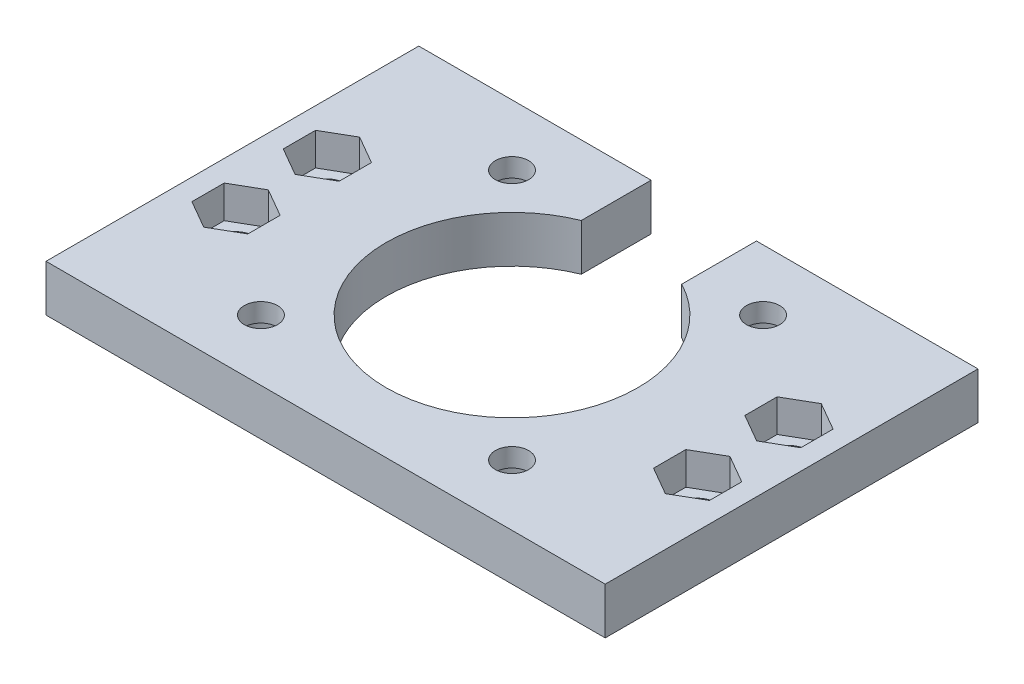
SolidWorks part; units mm, degrees
ref_plane "Front Plane" through (0, 0, 0) normal (0, 0, 1) x (1, 0, 0)
ref_plane "Top Plane" through (0, 0, 0) normal (0, 1, 0) x (1, 0, 0)
ref_plane "Right Plane" through (0, 0, 0) normal (1, 0, 0) x (0, 0, -1)
sketch "Sketch1" plane through (0, 0, 0) normal (0, 1, 0) x (1, 0, 0)
  line L1 (0, 0) -> (60, 0)
  line L2 (0, 0) -> (0, 40)
  line L3 (0, 40) -> (60, 40)
  line L4 (60, 0) -> (60, 40)
  dimension "D1" = 60
  dimension "D2" = 40
extrude "Boss-Extrude1" add sketch "Sketch1" along normal blind 5
sketch "Sketch2" plane through (0, 5, 0) normal (0, 1, 0) x (1, 0, 0)
  line L0 (30, 40) -> (30, 0)
  line L1 (60, 40) -> (0, 40) construction
  line L2 (0, 0) -> (60, 0) construction
  line L3 (30, 0) -> (30, 20)
  line L4 (30, 20) -> (60, 20)
  line L5 (60, 0) -> (60, 40) construction
  line L6 (60, 20) -> (0, 20)
  line L7 (0, 40) -> (0, 0) construction
  line L8 (54.8187, 24.9) -> (54.8187, 15.1) construction
  circle A0 centre (43.47, 33.47) radius 1.78
  circle A1 centre (16.53, 33.47) radius 1.78
  circle A2 centre (16.53, 6.53) radius 1.78
  circle A3 centre (43.47, 6.53) radius 1.78
  circle A4 centre (54.8187, 24.9) radius 1.905
  circle A5 centre (5.2887, 24.9) radius 1.905
  circle A6 centre (5.2887, 15.1) radius 1.905
  circle A7 centre (54.8187, 15.1) radius 1.905
  dimension "D1" = 3.56
  dimension "D2" = 13.47
  dimension "D3" = 13.47
  dimension "D6" = 3.81
  dimension "D7" = 4.9
  dimension "D10" = 2
  dimension "D9" = 9.8
  dimension "D4" = 2
  dimension "D5" = 2
  dimension "D8" = 2
extrude "Cut-Extrude1" cut sketch "Sketch2" along direction (0, -1, 0) on the side against the normal blind 10
sketch "Sketch3" plane through (0, 5, 0) normal (0, 1, 0) x (1, 0, 0)
  line L0 (30, 40) -> (30, 0)
  line L1 (60, 40) -> (0, 40) construction
  line L2 (0, 0) -> (60, 0) construction
  line L4 (24.925, 27.3478) -> (36.2301, 27.3478)
  line L5 (24.925, 27.3478) -> (24.925, 48.9338)
  line L6 (24.925, 48.9338) -> (36.2301, 48.9338)
  line L7 (36.2301, 27.3478) -> (36.2301, 48.9338)
  circle A0 centre (30, 20) radius 13.5
  line M12 (60, 40) -> (0, 40)
  dimension "D1" = 27
extrude "Cut-Extrude2" cut sketch "Sketch3" along direction (0, -1, 0) on the side against the normal through all contours L0 A0 L7 L4 | L5 A0 L0 L4 | A0 L7 L0 M12 | L7 A0 L0 L4 | L0 A0 L5 L4 | A0 L0 L5 M12
sketch "Sketch7" plane through (0, 0, 0) normal (0, -1, 0) x (-1, 0, 0)
  circle A0 centre (-43.47, 6.53) radius 4.5
  circle A1 centre (-16.53, 6.53) radius 4.5
  circle A2 centre (-16.53, 33.47) radius 4.5
  circle A3 centre (-43.47, 33.47) radius 4.5
  dimension "D1" = 9
  dimension "D2" = 2
extrude "Cut-Extrude5" cut sketch "Sketch7" against normal blind 3
sketch "Sketch8" plane through (0, 5, 0) normal (0, 1, 0) x (1, 0, 0)
  line L0 (5.2887, 18.5641) -> (2.2887, 16.8321)
  line L1 (54.8187, 11.6359) -> (57.8187, 13.3679)
  line L2 (57.8187, 13.3679) -> (57.8187, 16.8321)
  line L3 (57.8187, 16.8321) -> (54.8187, 18.5641)
  line L4 (54.8187, 18.5641) -> (51.8187, 16.8321)
  line L5 (51.8187, 16.8321) -> (51.8187, 13.3679)
  line L6 (51.8187, 13.3679) -> (54.8187, 11.6359)
  line L7 (8.2887, 16.8321) -> (5.2887, 18.5641)
  line L8 (8.2887, 13.3679) -> (8.2887, 16.8321)
  line L9 (5.2887, 11.6359) -> (8.2887, 13.3679)
  line L10 (2.2887, 13.3679) -> (5.2887, 11.6359)
  line L11 (2.2887, 16.8321) -> (2.2887, 13.3679)
  line L12 (5.2887, 28.3641) -> (2.2887, 26.6321)
  line L13 (8.2887, 26.6321) -> (5.2887, 28.3641)
  line L14 (8.2887, 23.1679) -> (8.2887, 26.6321)
  line L15 (5.2887, 21.4359) -> (8.2887, 23.1679)
  line L16 (2.2887, 23.1679) -> (5.2887, 21.4359)
  line L17 (2.2887, 26.6321) -> (2.2887, 23.1679)
  line L18 (54.8187, 28.3641) -> (51.8187, 26.6321)
  line L19 (57.8187, 26.6321) -> (54.8187, 28.3641)
  line L20 (57.8187, 23.1679) -> (57.8187, 26.6321)
  line L21 (54.8187, 21.4359) -> (57.8187, 23.1679)
  line L22 (51.8187, 23.1679) -> (54.8187, 21.4359)
  line L23 (51.8187, 26.6321) -> (51.8187, 23.1679)
  circle A0 centre (54.8187, 15.1) radius 3 construction
  circle A1 centre (5.2887, 15.1) radius 3 construction
  circle A2 centre (5.2887, 24.9) radius 3 construction
  circle A3 centre (54.8187, 24.9) radius 3 construction
  dimension "D1" = 2
  dimension "D2" = 2
extrude "Cut-Extrude6" cut sketch "Sketch8" against normal blind 3.5
